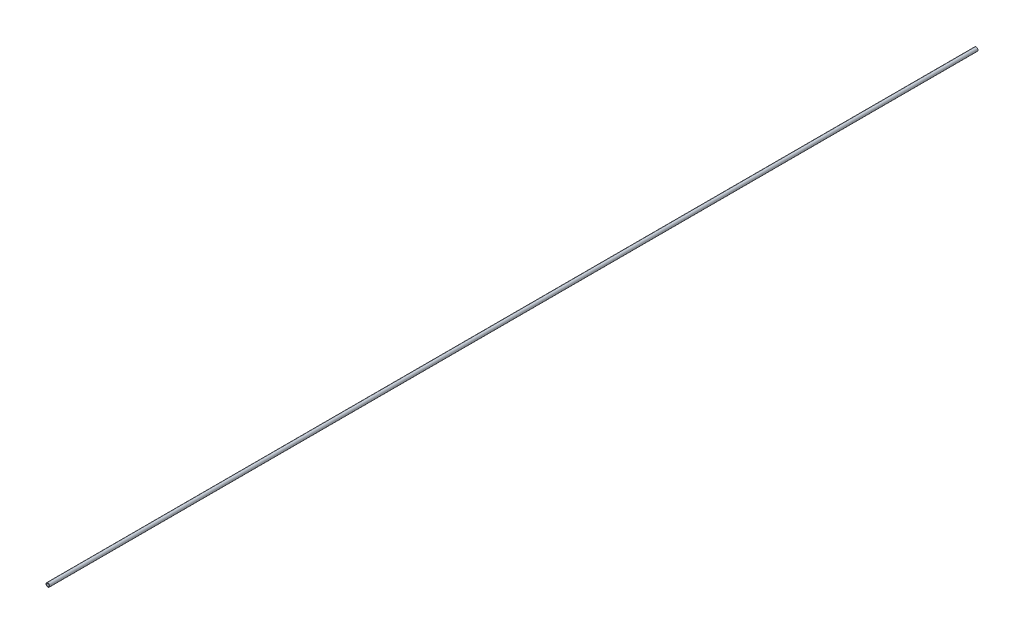
SolidWorks part; units mm, degrees
material "Hexcel AS4C (3000 Filaments)"
ref_plane "Front Plane" through (0, 0, 0) normal (0, 0, 1) x (1, 0, 0)
ref_plane "Top Plane" through (0, 0, 0) normal (0, 1, 0) x (1, 0, 0)
ref_plane "Right Plane" through (0, 0, 0) normal (1, 0, 0) x (0, 0, -1)
sketch "Sketch1" plane through (0, 0, 0) normal (0, 0, 1) x (1, 0, 0)
  circle A0 centre (0, 0) radius 2
  circle A1 centre (0, 0) radius 3
  dimension "D1" = 4
  dimension "D2" = 6
extrude "Boss-Extrude1" add sketch "Sketch1" along normal blind 1500
